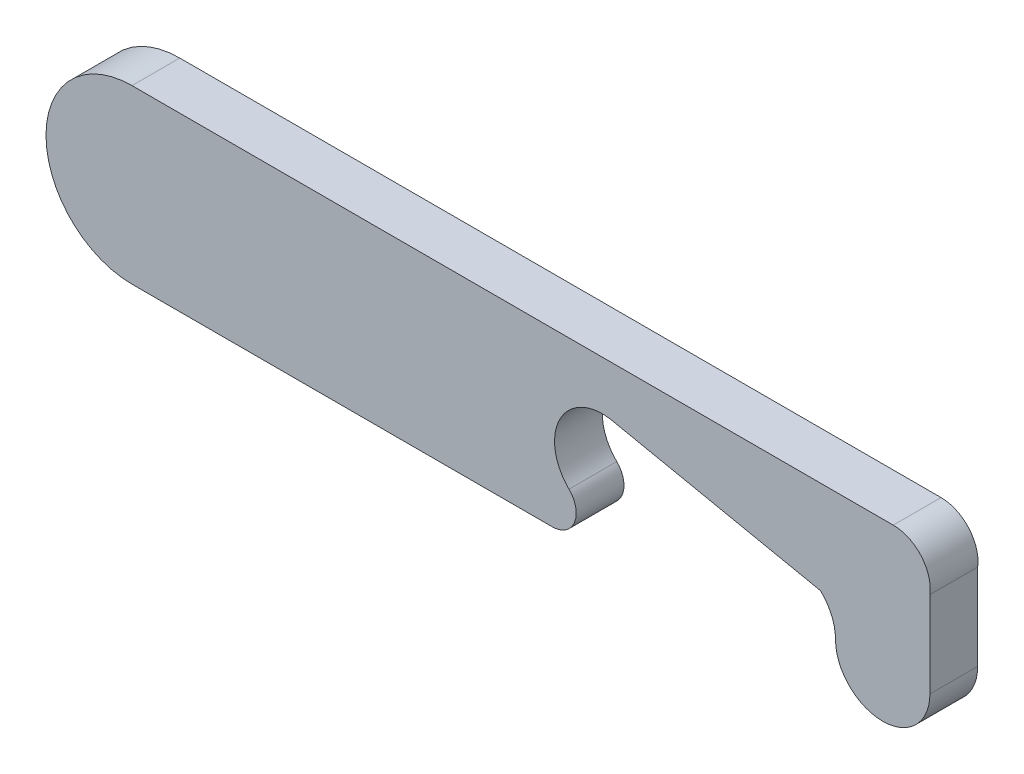
SolidWorks part; units mm, degrees
ref_plane "Front Plane" through (0, 0, 0) normal (0, 0, 1) x (1, 0, 0)
ref_plane "Top Plane" through (0, 0, 0) normal (0, 1, 0) x (1, 0, 0)
ref_plane "Right Plane" through (0, 0, 0) normal (1, 0, 0) x (0, 0, -1)
sketch "Sketch1" plane through (0, 0, 0) normal (0, 0, 1) x (1, 0, 0)
  line L0 (5907.5127, 7762.3379) -> (85590.0392, 7762.3379)
  line L1 (5907.5127, -10237.6621) -> (49907.5127, -10237.6621)
  line L2 (89426.8888, 3372.6088) -> (89426.8888, -5627.3912)
  line L3 (77975.854, -1988.2595) -> (55942.7258, 2571.4841)
  line L4 (77927.7242, -2080.418) -> (55924.558, 2473.125)
  line L5 (89526.8888, 3365.9312) -> (89526.8888, -5627.3912)
  line L6 (5907.5127, 7862.3379) -> (85590.0392, 7862.3379)
  line L7 (5907.5127, -10337.6621) -> (49907.5127, -10337.6621)
  line L8 (5907.5127, 8962.3379) -> (85590.0392, 8962.3379)
  line L9 (90626.8888, 3297.4177) -> (90626.8888, -5627.3912)
  line L10 (77375.2124, -3089.3845) -> (55726.3013, 1390.8456)
  line L11 (5907.5127, -11437.6621) -> (49907.5127, -11437.6621)
  line L12 (77322.5099, -3180.5967) -> (55708.446, 1292.4218)
  line L13 (5907.5127, -11537.6621) -> (49907.5127, -11537.6621)
  line L14 (5907.5127, 9062.3379) -> (85590.0392, 9062.3379)
  line L15 (90726.8888, 3291.5776) -> (90726.8888, -5627.3912)
  arc A0 (5907.5127, 7762.3379) -> (5907.5127, -10237.6621) centre (5907.5127, -1237.6621) ccw
  arc A1 (85590.0392, 7762.3379) -> (89426.8888, 3372.6088) centre (85590.0392, 3890.6711) cw
  arc A2 (89426.8888, -5627.3912) -> (79547.0465, -5627.3912) centre (84486.9677, -5627.3912) cw
  arc A3 (79547.0465, -5627.3912) -> (77975.854, -1988.2595) centre (74547.0465, -5627.3912) ccw
  arc A4 (49907.5127, -10237.6621) -> (51651.337, -5946.2725) centre (49907.5127, -7737.6621) ccw
  arc A5 (51651.337, -5946.2725) -> (55942.7258, 2571.4841) centre (55138.9856, -2363.4933) cw
  circle A6 centre (5907.5127, -1237.6621) radius 5342.8075
  arc A7 (51721.09, -5874.6169) -> (55924.558, 2473.125) centre (55138.9856, -2363.4933) cw
  arc A8 (79447.0465, -5627.3912) -> (77927.7242, -2080.418) centre (74547.0465, -5627.3912) ccw
  arc A9 (89526.8888, -5627.3912) -> (79447.0465, -5627.3912) centre (84486.9677, -5627.3912) cw
  arc A10 (85590.0392, 7862.3379) -> (89526.8888, 3365.9312) centre (85590.0392, 3890.6711) cw
  arc A11 (5907.5127, 7862.3379) -> (5907.5127, -10337.6621) centre (5907.5127, -1237.6621) ccw
  arc A12 (49907.5127, -10337.6621) -> (51721.09, -5874.6169) centre (49907.5127, -7737.6621) ccw
  arc A13 (85590.0392, 8962.3379) -> (90626.8888, 3297.4177) centre (85590.0392, 3890.6711) cw
  arc A14 (90626.8888, -5627.3912) -> (78347.0465, -5627.3912) centre (84486.9677, -5627.3912) cw
  arc A15 (78347.0465, -5627.3912) -> (77375.2124, -3089.3845) centre (74547.0465, -5627.3912) ccw
  arc A16 (52488.3727, -5086.4055) -> (55726.3013, 1390.8456) centre (55138.9856, -2363.4933) cw
  arc A17 (49907.5127, -11437.6621) -> (52488.3727, -5086.4055) centre (49907.5127, -7737.6621) ccw
  arc A18 (5907.5127, 8962.3379) -> (5907.5127, -11437.6621) centre (5907.5127, -1237.6621) ccw
  arc A19 (52558.1256, -5014.7499) -> (55708.446, 1292.4218) centre (55138.9856, -2363.4933) cw
  arc A20 (49907.5127, -11537.6621) -> (52558.1256, -5014.7499) centre (49907.5127, -7737.6621) ccw
  arc A21 (5907.5127, 9062.3379) -> (5907.5127, -11537.6621) centre (5907.5127, -1237.6621) ccw
  arc A22 (85590.0392, 9062.3379) -> (90726.8888, 3291.5776) centre (85590.0392, 3890.6711) cw
  arc A23 (90726.8888, -5627.3912) -> (78247.0465, -5627.3912) centre (84486.9677, -5627.3912) cw
  arc A24 (78247.0465, -5627.3912) -> (77322.5099, -3180.5967) centre (74547.0465, -5627.3912) ccw
  dimension "D1" = 1200
extrude "Boss-Extrude2" add sketch "Sketch1" along normal blind 5000 contours A1 L2 A2 A3 L3 A5 A4 L1 A0 L0
sketch "Sketch3" plane through (0, 0, 5000) normal (0, 0, 1) x (1, 0, 0)
  line L8 (85590.0392, 6562.3379) -> (5907.5127, 6562.3379)
  line L9 (5907.5127, -9037.6621) -> (49907.5127, -9037.6621)
  line L10 (56162.213, 3751.4888) -> (78532.4543, -878.0202)
  line L11 (88226.8888, -5627.3912) -> (88226.8888, 3460.7556)
  line L12 (85590.0392, 6562.3379) -> (5907.5127, 6562.3379)
  line L13 (5907.5127, -9037.6621) -> (49907.5127, -9037.6621)
  line L14 (56162.213, 3751.4888) -> (78532.4543, -878.0202)
  line L15 (88226.8888, -5627.3912) -> (88226.8888, 3460.7556)
  arc A12 (5907.5127, 6562.3379) -> (5907.5127, -9037.6621) centre (5907.5127, -1237.6621) ccw
  arc A13 (49907.5127, -9037.6621) -> (50814.3013, -6806.1395) centre (49907.5127, -7737.6621) ccw
  arc A14 (56162.213, 3751.4888) -> (50814.3013, -6806.1395) centre (55138.9856, -2363.4933) ccw
  arc A15 (80747.0465, -5627.3912) -> (78532.4543, -878.0202) centre (74547.0465, -5627.3912) ccw
  arc A16 (80747.0465, -5627.3912) -> (88226.8888, -5627.3912) centre (84486.9677, -5627.3912) ccw
  arc A17 (88226.8888, 3460.7556) -> (85590.0392, 6562.3379) centre (85590.0392, 3890.6711) ccw
  arc A18 (5907.5127, 6562.3379) -> (5907.5127, -9037.6621) centre (5907.5127, -1237.6621) ccw
  arc A19 (49907.5127, -9037.6621) -> (50814.3013, -6806.1395) centre (49907.5127, -7737.6621) ccw
  arc A20 (56162.213, 3751.4888) -> (50814.3013, -6806.1395) centre (55138.9856, -2363.4933) ccw
  arc A21 (80747.0465, -5627.3912) -> (78532.4543, -878.0202) centre (74547.0465, -5627.3912) ccw
  arc A22 (80747.0465, -5627.3912) -> (88226.8888, -5627.3912) centre (84486.9677, -5627.3912) ccw
  arc A23 (88226.8888, 3460.7556) -> (85590.0392, 6562.3379) centre (85590.0392, 3890.6711) ccw
  dimension "D1" = 1200
extrude "Boss-Extrude6" add sketch "Sketch3" against normal blind 1212 contours A18 L13 A19 A20 L14 A21 A22 L15 A23 L12
sketch3d "3DSketch1"
  line L0 (88426.8888, -5627.3912, 5000) -> (88426.8888, 3439.8153, 5000)
  line L1 (85590.0392, 6762.3379, 5000) -> (5907.5127, 6762.3379, 5000)
  line L2 (5907.5127, -9237.6621, 5000) -> (49907.5127, -9237.6621, 5000)
  line L3 (56124.51, 3555.0535, 5000) -> (78455.6391, -1066.3612, 5000)
  line L4 (88426.8888, -5627.3912, 5000) -> (88426.8888, 3439.8153, 5000)
  line L5 (85590.0392, 6762.3379, 5000) -> (5907.5127, 6762.3379, 5000)
  line L6 (5907.5127, -9237.6621, 5000) -> (49907.5127, -9237.6621, 5000)
  line L7 (56124.51, 3555.0535, 5000) -> (78455.6391, -1066.3612, 5000)
  spline S0 degree 5 poles (88025.4847, 466.9342, 5000) (88107.5619, 1074.8306, 5000) (88189.6419, 1682.7273, 5000) (88271.7218, 2290.624, 5000) (88355.6023, 2911.8559, 5000) (88439.4828, 3533.0879, 5000) (88441.2434, 3546.4282, 5000) (88447.6094, 3596.9969, 5000) (88452.2549, 3647.7815, 5000) (88454.8905, 3685.2412, 5000) (88460.1742, 3784.3107, 5000) (88462.0626, 3883.4754, 5000) (88461.7751, 3945.0906, 5000) (88457.6512, 4078.8264, 5000) (88445.2189, 4212.1377, 5000) (88436.1661, 4283.8517, 5000) (88413.5231, 4426.6259, 5000) (88382.1075, 4567.6862, 5000) (88364.2131, 4637.6976, 5000) (88324.0642, 4776.5019, 5000) (88275.2213, 4912.5083, 5000) (88248.666, 4979.7228, 5000) (88191.3666, 5112.3967, 5000) (88125.8478, 5241.2037, 5000) (88091.0782, 5304.557, 5000) (88017.6078, 5428.9969, 5000) (87936.4531, 5548.5695, 5000) (87894.011, 5607.062, 5000) (87805.5097, 5721.3051, 5000) (87709.9992, 5829.7565, 5000) (87660.5568, 5882.4645, 5000) (87558.4276, 5984.7059, 5000) (87450.0701, 6080.319, 5000) (87394.4075, 6126.4088, 5000) (87280.2617, 6215.0353, 5000) (87160.7675, 6296.3168, 5000) (87099.7638, 6335.0665, 5000) (86975.4044, 6408.6741, 5000) (86846.663, 6474.2787, 5000) (86781.2824, 6505.0538, 5000) (86648.6725, 6562.4967, 5000) (86512.7073, 6611.6191, 5000) (86443.9787, 6634.0181, 5000) (86305.215, 6674.3273, 5000) (86164.2091, 6705.3306, 5000) (86093.231, 6718.6845, 5000) (85974.2843, 6737.6593, 5000) (85854.4917, 6751.6614, 5000) (85806.4774, 6756.1979, 5000) (85441.4271, 6780.5237, 5000) (85075.1689, 6712.4891, 5000) (84760.2357, 6889.881, 5000) (84452.3983, 7609.8432, 5000) (84155.66, 9178.4791, 5000) knots -0.604775 -0.604775 -0.604775 -0.604775 -0.604775 -0.604775 0.013549 0.013549 0.013549 0.027113 0.027113 0.027113 0.064927 0.064927 0.064927 0.126992 0.126992 0.126992 0.199742 0.199742 0.199742 0.272493 0.272493 0.272493 0.345244 0.345244 0.345244 0.417994 0.417994 0.417994 0.490745 0.490745 0.490745 0.563496 0.563496 0.563496 0.636246 0.636246 0.636246 0.708997 0.708997 0.708997 0.781748 0.781748 0.781748 0.854499 0.854499 0.854499 0.927249 0.927249 0.927249 0.97575 0.97575 0.97575 1.295543 1.295543 1.295543 1.295543 1.295543 1.295543 only from (88426.8888, 3439.8153, 5000) to (85590.0392, 6762.3379, 5000)
  spline S1 degree 5 poles (8331.8503, 8203.4476, 5000) (7789.052, 7220.1856, 5000) (7238.9422, 6795.9859, 5000) (6684.2923, 6718.9344, 5000) (5993.6489, 6791.1523, 5000) (5304.5506, 6745.2329, 5000) (5170.7906, 6732.595, 5000) (4837.0678, 6693.5874, 5000) (4505.7016, 6640.7265, 5000) (4307.968, 6603.5247, 5000) (3915.1485, 6517.1547, 5000) (3528.575, 6404.8597, 5000) (3337.1082, 6342.4598, 5000) (2958.3313, 6205.6126, 5000) (2588.9014, 6045.586, 5000) (2406.7616, 5959.8516, 5000) (2048.1089, 5777.0878, 5000) (1701.6637, 5572.0289, 5000) (1531.7173, 5464.0785, 5000) (1198.8257, 5237.6413, 5000) (880.8339, 4990.7422, 5000) (725.7672, 4862.3436, 5000) (423.9006, 4595.9809, 5000) (139.3845, 4311.1528, 5000) (1.6455, 4164.3166, 5000) (-264.4311, 3862.1885, 5000) (-510.979, 3543.9259, 5000) (-629.2149, 3380.9755, 5000) (-855.2993, 3047.8655, 5000) (-1059.9855, 2701.1951, 5000) (-1156.8513, 2524.7024, 5000) (-1339.3735, 2165.8673, 5000) (-1498.9657, 1796.2632, 5000) (-1572.9318, 1609.0157, 5000) (-1709.0094, 1230.1229, 5000) (-1820.9875, 843.4219, 5000) (-1870.8859, 648.3762, 5000) (-1958.37, 255.4088, 5000) (-2020.9657, -142.2828, 5000) (-2046.0084, -342.0464, 5000) (-2083.5176, -742.8829, 5000) (-2095.7424, -1145.2849, 5000) (-2095.5339, -1346.612, 5000) (-2082.4759, -1748.9878, 5000) (-2044.1367, -2149.7458, 5000) (-2018.6804, -2349.4571, 5000) (-1955.2613, -2747.0183, 5000) (-1866.9637, -3139.8037, 5000) (-1816.6615, -3334.7455, 5000) (-1703.8828, -3721.2139, 5000) (-1567.021, -4099.8241, 5000) (-1492.6672, -4286.918, 5000) (-1332.31, -4656.1908, 5000) (-1149.0452, -5014.6472, 5000) (-1051.8141, -5190.9389, 5000) (-846.4105, -5537.1847, 5000) (-619.6368, -5869.8259, 5000) (-501.0636, -6032.5311, 5000) (-253.8573, -6350.2825, 5000) (12.8444, -6651.8589, 5000) (150.8871, -6798.4096, 5000) (435.9925, -7082.6479, 5000) (738.41, -7348.3849, 5000) (893.7423, -7476.4621, 5000) (1212.2446, -7722.7022, 5000) (1545.6043, -7948.4498, 5000) (1715.7738, -8056.0481, 5000) (2062.643, -8260.389, 5000) (2421.6738, -8442.4091, 5000) (2603.9909, -8527.766, 5000) (2973.7513, -8687.0274, 5000) (3352.809, -8823.0923, 5000) (3544.404, -8885.0965, 5000) (3930.1494, -8996.2845, 5000) (4322.0591, -9081.6683, 5000) (4518.7729, -9118.3208, 5000) (4848.0365, -9170.3036, 5000) (5179.5933, -9208.6088, 5000) (5312.2591, -9220.99, 5000) (5997.6873, -9266.0479, 5000) (6684.6307, -9194.3643, 5000) (7236.6852, -9272.9102, 5000) (7784.2158, -9700.0124, 5000) (8324.4681, -10687.8892, 5000) knots -0.097275 -0.097275 -0.097275 -0.097275 -0.097275 -0.097275 0.013342 0.013342 0.013342 0.040026 0.040026 0.040026 0.080053 0.080053 0.080053 0.120079 0.120079 0.120079 0.160105 0.160105 0.160105 0.200132 0.200132 0.200132 0.240158 0.240158 0.240158 0.280184 0.280184 0.280184 0.320211 0.320211 0.320211 0.360237 0.360237 0.360237 0.400263 0.400263 0.400263 0.44029 0.44029 0.44029 0.480316 0.480316 0.480316 0.520342 0.520342 0.520342 0.560369 0.560369 0.560369 0.600395 0.600395 0.600395 0.640421 0.640421 0.640421 0.680448 0.680448 0.680448 0.720474 0.720474 0.720474 0.7605 0.7605 0.7605 0.800527 0.800527 0.800527 0.840553 0.840553 0.840553 0.880579 0.880579 0.880579 0.920606 0.920606 0.920606 0.960413 0.960413 0.960413 0.986877 0.986877 0.986877 1.09698 1.09698 1.09698 1.09698 1.09698 1.09698 only from (5907.5127, 6762.3379, 5000) to (5907.5127, -9237.6621, 5000)
  spline S2 degree 5 poles (48951.5613, -11979.9891, 5000) (49139.6087, -10230.3566, 5000) (49339.8221, -9410.9602, 5000) (49547.8891, -9192.0776, 5000) (49784.7113, -9250.1717, 5000) (50020.5681, -9234.4549, 5000) (50045.6481, -9232.0853, 5000) (50108.2211, -9224.7714, 5000) (50170.3523, -9214.86, 5000) (50207.4273, -9207.8847, 5000) (50281.081, -9191.6903, 5000) (50353.5635, -9170.635, 5000) (50389.4635, -9158.935, 5000) (50460.4842, -9133.2761, 5000) (50529.7523, -9103.2711, 5000) (50563.9035, -9087.1959, 5000) (50631.1509, -9052.9277, 5000) (50696.1094, -9014.4792, 5000) (50727.9743, -8994.2385, 5000) (50790.3915, -8951.7815, 5000) (50850.015, -8905.4879, 5000) (50879.09, -8881.4132, 5000) (50935.69, -8831.4702, 5000) (50989.0367, -8778.0649, 5000) (51014.8628, -8750.5331, 5000) (51064.7522, -8693.8841, 5000) (51110.9799, -8634.2099, 5000) (51133.1491, -8603.6567, 5000) (51175.5399, -8541.1985, 5000) (51213.9186, -8476.1978, 5000) (51232.081, -8443.1055, 5000) (51266.3038, -8375.8239, 5000) (51296.2274, -8306.5231, 5000) (51310.096, -8271.4142, 5000) (51335.6106, -8200.3718, 5000) (51356.6065, -8127.8653, 5000) (51365.9625, -8091.2943, 5000) (51382.3657, -8017.6129, 5000) (51394.1023, -7943.0458, 5000) (51398.7978, -7905.5902, 5000) (51405.8308, -7830.4333, 5000) (51408.1232, -7754.9826, 5000) (51408.0843, -7717.2337, 5000) (51405.6358, -7641.7883, 5000) (51398.4462, -7566.6473, 5000) (51393.6727, -7529.2018, 5000) (51381.7819, -7454.6588, 5000) (51365.23, -7381.0074, 5000) (51355.7998, -7344.4542, 5000) (51334.6528, -7271.9925, 5000) (51308.9765, -7201.0188, 5000) (51295.0298, -7165.9443, 5000) (51264.9668, -7096.7015, 5000) (51230.6593, -7029.4327, 5000) (51212.4485, -6996.3566, 5000) (51174.9172, -6933.13, 5000) (51133.404, -6872.5157, 5000) (51112.3439, -6843.5984, 5000) (51076.3641, -6796.8378, 5000) (51038.544, -6751.484, 5000) (51023.3108, -6733.954, 5000) (50872.9498, -6569.5185, 5000) (50676.7719, -6451.0302, 5000) (50694.4894, -6150.8678, 5000) (51135.9063, -5425.8022, 5000) (52231.2577, -4044.9441, 5000) knots -0.279215 -0.279215 -0.279215 -0.279215 -0.279215 -0.279215 0.017688 0.017688 0.017688 0.053065 0.053065 0.053065 0.10613 0.10613 0.10613 0.159195 0.159195 0.159195 0.21226 0.21226 0.21226 0.265325 0.265325 0.265325 0.31839 0.31839 0.31839 0.371455 0.371455 0.371455 0.42452 0.42452 0.42452 0.477585 0.477585 0.477585 0.53065 0.53065 0.53065 0.583715 0.583715 0.583715 0.63678 0.63678 0.63678 0.689845 0.689845 0.689845 0.74291 0.74291 0.74291 0.795976 0.795976 0.795976 0.849041 0.849041 0.849041 0.902106 0.902106 0.902106 0.952425 0.952425 0.952425 0.985057 0.985057 0.985057 1.265751 1.265751 1.265751 1.265751 1.265751 1.265751 only from (49907.5127, -9237.6621, 5000) to (50953.8073, -6662.8283, 5000)
  spline S3 degree 5 poles (51250.0046, -9422.1078, 5000) (51742.7709, -8246.7236, 5000) (51767.5921, -7539.6368, 5000) (51498.5986, -7126.5862, 5000) (51028.9011, -6772.177, 5000) (50638.7137, -6338.1979, 5000) (50573.4403, -6261.4299, 5000) (50414.4987, -6065.8803, 5000) (50264.071, -5864.1187, 5000) (50177.2676, -5740.682, 5000) (50011.344, -5488.7628, 5000) (49862.3397, -5226.1787, 5000) (49792.0866, -5092.4786, 5000) (49660.1167, -4820.7785, 5000) (49545.2963, -4541.5113, 5000) (49492.2631, -4400.1502, 5000) (49395.1295, -4114.3017, 5000) (49316.2199, -3822.8577, 5000) (49281.3618, -3675.9363, 5000) (49220.9202, -3380.0938, 5000) (49179.1907, -3081.0495, 5000) (49163.0266, -2930.9232, 5000) (49140.1454, -2629.8547, 5000) (49136.2486, -2327.9394, 5000) (49139.0423, -2176.9694, 5000) (49154.1057, -1875.4034, 5000) (49188.105, -1575.3829, 5000) (49209.81, -1425.9558, 5000) (49262.5741, -1128.6614, 5000) (49333.932, -835.2738, 5000) (49374.2063, -689.7486, 5000) (49463.8394, -401.4186, 5000) (49571.4292, -119.2969, 5000) (49629.6366, 20.0283, 5000) (49754.723, 294.8403, 5000) (49896.8457, 561.241, 5000) (49972.067, 692.1661, 5000) (50130.6314, 949.1204, 5000) (50305.0427, 1195.5933, 5000) (50396.0901, 1316.0507, 5000) (50585.6286, 1551.0898, 5000) (50789.5743, 1773.743, 5000) (50895.0101, 1881.8306, 5000) (51112.5295, 2091.2429, 5000) (51342.789, 2286.5593, 5000) (51460.9481, 2380.5699, 5000) (51703.0136, 2561.0486, 5000) (51955.9511, 2725.9478, 5000) (52084.9677, 2804.3982, 5000) (52347.7567, 2953.0924, 5000) (52619.3767, 3084.9564, 5000) (52757.2132, 3146.6028, 5000) (53036.5761, 3261.168, 5000) (53322.5936, 3357.966, 5000) (53467.0747, 3401.8537, 5000) (53758.599, 3480.4671, 5000) (54054.4821, 3540.4787, 5000) (54203.3207, 3565.8443, 5000) (54502.4069, 3607.3159, 5000) (54803.5401, 3630.3094, 5000) (54954.4068, 3637.0146, 5000) (55212.4714, 3639.9918, 5000) (55470.1749, 3627.9595, 5000) (55577.0231, 3620.6345, 5000) (55740.2773, 3606.2487, 5000) (55903.0379, 3587.5975, 5000) (55959.3434, 3580.4727, 5000) (56021.9303, 3571.6306, 5000) (56084.3263, 3561.5938, 5000) (56090.7093, 3560.5585, 5000) (56691.8277, 3462.6567, 5000) (57292.9461, 3364.755, 5000) (57887.6823, 3267.8926, 5000) (58482.3908, 3171.0307, 5000) (59085.5645, 3074.0754, 5000) knots -0.142129 -0.142129 -0.142129 -0.142129 -0.142129 -0.142129 0.016537 0.016537 0.016537 0.049611 0.049611 0.049611 0.099222 0.099222 0.099222 0.148832 0.148832 0.148832 0.198443 0.198443 0.198443 0.248054 0.248054 0.248054 0.297665 0.297665 0.297665 0.347275 0.347275 0.347275 0.396886 0.396886 0.396886 0.446497 0.446497 0.446497 0.496108 0.496108 0.496108 0.545718 0.545718 0.545718 0.595329 0.595329 0.595329 0.64494 0.64494 0.64494 0.694551 0.694551 0.694551 0.744162 0.744162 0.744162 0.793772 0.793772 0.793772 0.843383 0.843383 0.843383 0.892994 0.892994 0.892994 0.942605 0.942605 0.942605 0.977806 0.977806 0.977806 0.99647 0.99647 0.99647 0.998598 0.998598 0.998598 1.196839 1.196839 1.196839 1.196839 1.196839 1.196839 only from (50953.8073, -6662.8283, 5000) to (56124.51, 3555.0535, 5000)
  spline S4 degree 5 poles (76272.216, 990.8707, 5000) (76750.0959, 540.6099, 5000) (77227.9758, 90.3491, 5000) (77705.8557, -359.9116, 5000) (78201.3951, -826.8113, 5000) (78696.9345, -1293.7109, 5000) (78714.551, -1310.3947, 5000) (78785.9288, -1378.6911, 5000) (78855.1659, -1449.2212, 5000) (78906.3562, -1503.478, 5000) (79040.9462, -1650.7948, 5000) (79170.603, -1802.4318, 5000) (79249.5618, -1899.19, 5000) (79418.4048, -2117.1637, 5000) (79573.6566, -2345.2415, 5000) (79654.5211, -2472.7992, 5000) (79808.0466, -2732.9004, 5000) (79945.1002, -3001.909, 5000) (80009.4274, -3138.4877, 5000) (80129.5193, -3415.4885, 5000) (80232.1598, -3699.5661, 5000) (80278.9526, -3843.1732, 5000) (80363.1546, -4133.1225, 5000) (80427.931, -4427.7383, 5000) (80455.8343, -4576.0365, 5000) (80495.4843, -4824.5569, 5000) (80524.7402, -5074.8487, 5000) (80534.2185, -5175.169, 5000) (80573.0209, -5757.4959, 5000) (80499.344, -6341.2883, 5000) (80607.7005, -6822.178, 5000) (81131.7304, -7297.652, 5000) (82317.7822, -7764.5005, 5000) knots -0.580161 -0.580161 -0.580161 -0.580161 -0.580161 -0.580161 0.05473 0.05473 0.05473 0.078192 0.078192 0.078192 0.150258 0.150258 0.150258 0.270929 0.270929 0.270929 0.416744 0.416744 0.416744 0.562558 0.562558 0.562558 0.708372 0.708372 0.708372 0.854186 0.854186 0.854186 0.951395 0.951395 0.951395 1.417761 1.417761 1.417761 1.417761 1.417761 1.417761 only from (78455.6391, -1066.3612, 5000) to (80547.0465, -5627.3912, 5000)
  spline S5 degree 5 poles (78368.1803, -3915.8644, 5000) (79797.4706, -4277.739, 5000) (80445.4406, -4649.7544, 5000) (80596.8291, -5028.215, 5000) (80525.9705, -5475.0312, 5000) (80555.2574, -5920.5477, 5000) (80561.355, -5985.8843, 5000) (80580.2199, -6149.1727, 5000) (80605.8209, -6311.3318, 5000) (80623.8719, -6408.2114, 5000) (80665.9226, -6601.2231, 5000) (80720.6816, -6791.1989, 5000) (80751.2181, -6885.5575, 5000) (80818.2287, -7072.2398, 5000) (80896.6634, -7254.3431, 5000) (80938.7008, -7344.1325, 5000) (81028.3439, -7520.9516, 5000) (81128.9798, -7691.7812, 5000) (81181.9709, -7775.5881, 5000) (81293.1494, -7939.7644, 5000) (81414.4202, -8096.6237, 5000) (81477.497, -8173.1233, 5000) (81608.3698, -8322.0609, 5000) (81748.3544, -8462.4725, 5000) (81820.5291, -8530.4572, 5000) (81969.0525, -8661.8051, 5000) (82125.542, -8783.5518, 5000) (82205.6727, -8841.9479, 5000) (82369.4952, -8953.6318, 5000) (82540.0178, -9054.791, 5000) (82626.8398, -9102.6764, 5000) (82803.376, -9192.9325, 5000) (82985.2392, -9271.9068, 5000) (83077.3811, -9308.5253, 5000) (83263.8429, -9375.9284, 5000) (83454.1748, -9431.4708, 5000) (83550.1817, -9456.2441, 5000) (83743.6247, -9499.7299, 5000) (83939.4196, -9530.9631, 5000) (84037.7755, -9543.5001, 5000) (84235.1448, -9562.3818, 5000) (84433.3109, -9568.8127, 5000) (84532.4626, -9568.9154, 5000) (84730.6416, -9562.8948, 5000) (84928.0496, -9544.4219, 5000) (85026.4312, -9532.0886, 5000) (85222.2904, -9501.2609, 5000) (85415.823, -9458.1758, 5000) (85511.881, -9433.6013, 5000) (85702.3275, -9378.4532, 5000) (85888.9284, -9311.4364, 5000) (85981.146, -9275.0088, 5000) (86163.1724, -9196.4112, 5000) (86339.8951, -9106.5208, 5000) (86426.816, -9058.8153, 5000) (86597.5478, -8958.0094, 5000) (86761.6012, -8846.6651, 5000) (86841.8527, -8788.435, 5000) (86998.5939, -8667.0126, 5000) (87147.389, -8535.9725, 5000) (87219.7043, -8468.1375, 5000) (87359.9794, -8328.0161, 5000) (87491.1604, -8179.3497, 5000) (87554.3954, -8102.9809, 5000) (87675.9908, -7946.3731, 5000) (87787.5089, -7782.4273, 5000) (87840.6734, -7698.7303, 5000) (87941.6629, -7528.1095, 5000) (88031.6722, -7351.4766, 5000) (88073.8956, -7261.7745, 5000) (88152.7071, -7079.8339, 5000) (88220.103, -6893.2901, 5000) (88250.8344, -6798.9945, 5000) (88306.1385, -6608.6109, 5000) (88348.6749, -6415.1512, 5000) (88366.9964, -6317.7693, 5000) (88393.0299, -6154.5747, 5000) (88412.2408, -5990.2195, 5000) (88418.4648, -5924.344, 5000) (88448.3211, -5476.2995, 5000) (88376.7701, -5026.9287, 5000) (88526.822, -4646.4701, 5000) (89172.7625, -4272.4968, 5000) (90599.4101, -3908.7337, 5000) knots -0.140653 -0.140653 -0.140653 -0.140653 -0.140653 -0.140653 0.013123 0.013123 0.013123 0.039587 0.039587 0.039587 0.079394 0.079394 0.079394 0.119421 0.119421 0.119421 0.159447 0.159447 0.159447 0.199473 0.199473 0.199473 0.2395 0.2395 0.2395 0.279526 0.279526 0.279526 0.319552 0.319552 0.319552 0.359579 0.359579 0.359579 0.399605 0.399605 0.399605 0.439631 0.439631 0.439631 0.479658 0.479658 0.479658 0.519684 0.519684 0.519684 0.55971 0.55971 0.55971 0.599737 0.599737 0.599737 0.639763 0.639763 0.639763 0.679789 0.679789 0.679789 0.719816 0.719816 0.719816 0.759842 0.759842 0.759842 0.799868 0.799868 0.799868 0.839895 0.839895 0.839895 0.879921 0.879921 0.879921 0.919947 0.919947 0.919947 0.959974 0.959974 0.959974 0.986658 0.986658 0.986658 1.14124 1.14124 1.14124 1.14124 1.14124 1.14124 only from (80547.0465, -5627.3912, 5000) to (88426.8888, -5627.3912, 5000)
  spline S6 degree 5 poles (88426.8888, 3439.8153, 5000) (88428.6874, 3453.1357, 5000) (88430.486, 3466.4562, 5000) (88432.2845, 3479.7766, 5000) (88435.8836, 3506.4322, 5000) (88439.4828, 3533.0879, 5000) (88441.2434, 3546.4282, 5000) (88447.6094, 3596.9969, 5000) (88452.2549, 3647.7815, 5000) (88454.8905, 3685.2412, 5000) (88460.1742, 3784.3107, 5000) (88462.0626, 3883.4754, 5000) (88461.7751, 3945.0906, 5000) (88457.6512, 4078.8264, 5000) (88445.2189, 4212.1377, 5000) (88436.1661, 4283.8517, 5000) (88413.5231, 4426.6259, 5000) (88382.1075, 4567.6862, 5000) (88364.2131, 4637.6976, 5000) (88324.0642, 4776.5019, 5000) (88275.2213, 4912.5083, 5000) (88248.666, 4979.7228, 5000) (88191.3666, 5112.3967, 5000) (88125.8478, 5241.2037, 5000) (88091.0782, 5304.557, 5000) (88017.6078, 5428.9969, 5000) (87936.4531, 5548.5695, 5000) (87894.011, 5607.062, 5000) (87805.5097, 5721.3051, 5000) (87709.9992, 5829.7565, 5000) (87660.5568, 5882.4645, 5000) (87558.4276, 5984.7059, 5000) (87450.0701, 6080.319, 5000) (87394.4075, 6126.4088, 5000) (87280.2617, 6215.0353, 5000) (87160.7675, 6296.3168, 5000) (87099.7638, 6335.0665, 5000) (86975.4044, 6408.6741, 5000) (86846.663, 6474.2787, 5000) (86781.2824, 6505.0538, 5000) (86648.6725, 6562.4967, 5000) (86512.7073, 6611.6191, 5000) (86443.9787, 6634.0181, 5000) (86305.215, 6674.3273, 5000) (86164.2091, 6705.3306, 5000) (86093.231, 6718.6845, 5000) (85974.2843, 6737.6593, 5000) (85854.4917, 6751.6614, 5000) (85806.4774, 6756.1979, 5000) (85734.3674, 6761.0031, 5000) (85662.2103, 6762.2044, 5000) (85638.1544, 6762.3379, 5000) (85614.0968, 6762.3379, 5000) (85590.0392, 6762.3379, 5000) knots 0 0 0 0 0 0 0.013549 0.013549 0.013549 0.027113 0.027113 0.027113 0.064927 0.064927 0.064927 0.126992 0.126992 0.126992 0.199742 0.199742 0.199742 0.272493 0.272493 0.272493 0.345244 0.345244 0.345244 0.417994 0.417994 0.417994 0.490745 0.490745 0.490745 0.563496 0.563496 0.563496 0.636246 0.636246 0.636246 0.708997 0.708997 0.708997 0.781748 0.781748 0.781748 0.854499 0.854499 0.854499 0.927249 0.927249 0.927249 0.97575 0.97575 0.97575 1 1 1 1 1 1
  spline S7 degree 5 poles (5907.5127, 6762.3379, 5000) (5840.4921, 6762.3379, 5000) (5773.4714, 6762.3379, 5000) (5706.4556, 6761.966, 5000) (5505.4375, 6758.6194, 5000) (5304.5506, 6745.2329, 5000) (5170.7906, 6732.595, 5000) (4837.0678, 6693.5874, 5000) (4505.7016, 6640.7265, 5000) (4307.968, 6603.5247, 5000) (3915.1485, 6517.1547, 5000) (3528.575, 6404.8597, 5000) (3337.1082, 6342.4598, 5000) (2958.3313, 6205.6126, 5000) (2588.9014, 6045.586, 5000) (2406.7616, 5959.8516, 5000) (2048.1089, 5777.0878, 5000) (1701.6637, 5572.0289, 5000) (1531.7173, 5464.0785, 5000) (1198.8257, 5237.6413, 5000) (880.8339, 4990.7422, 5000) (725.7672, 4862.3436, 5000) (423.9006, 4595.9809, 5000) (139.3845, 4311.1528, 5000) (1.6455, 4164.3166, 5000) (-264.4311, 3862.1885, 5000) (-510.979, 3543.9259, 5000) (-629.2149, 3380.9755, 5000) (-855.2993, 3047.8655, 5000) (-1059.9855, 2701.1951, 5000) (-1156.8513, 2524.7024, 5000) (-1339.3735, 2165.8673, 5000) (-1498.9657, 1796.2632, 5000) (-1572.9318, 1609.0157, 5000) (-1709.0094, 1230.1229, 5000) (-1820.9875, 843.4219, 5000) (-1870.8859, 648.3762, 5000) (-1958.37, 255.4088, 5000) (-2020.9657, -142.2828, 5000) (-2046.0084, -342.0464, 5000) (-2083.5176, -742.8829, 5000) (-2095.7424, -1145.2849, 5000) (-2095.5339, -1346.612, 5000) (-2082.4759, -1748.9878, 5000) (-2044.1367, -2149.7458, 5000) (-2018.6804, -2349.4571, 5000) (-1955.2613, -2747.0183, 5000) (-1866.9637, -3139.8037, 5000) (-1816.6615, -3334.7455, 5000) (-1703.8828, -3721.2139, 5000) (-1567.021, -4099.8241, 5000) (-1492.6672, -4286.918, 5000) (-1332.31, -4656.1908, 5000) (-1149.0452, -5014.6472, 5000) (-1051.8141, -5190.9389, 5000) (-846.4105, -5537.1847, 5000) (-619.6368, -5869.8259, 5000) (-501.0636, -6032.5311, 5000) (-253.8573, -6350.2825, 5000) (12.8444, -6651.8589, 5000) (150.8871, -6798.4096, 5000) (435.9925, -7082.6479, 5000) (738.41, -7348.3849, 5000) (893.7423, -7476.4621, 5000) (1212.2446, -7722.7022, 5000) (1545.6043, -7948.4498, 5000) (1715.7738, -8056.0481, 5000) (2062.643, -8260.389, 5000) (2421.6738, -8442.4091, 5000) (2603.9909, -8527.766, 5000) (2973.7513, -8687.0274, 5000) (3352.809, -8823.0923, 5000) (3544.404, -8885.0965, 5000) (3930.1494, -8996.2845, 5000) (4322.0591, -9081.6683, 5000) (4518.7729, -9118.3208, 5000) (4848.0365, -9170.3036, 5000) (5179.5933, -9208.6088, 5000) (5312.2591, -9220.99, 5000) (5510.947, -9234.0511, 5000) (5709.7622, -9237.3028, 5000) (5775.6759, -9237.6621, 5000) (5841.5943, -9237.6621, 5000) (5907.5127, -9237.6621, 5000) knots 0 0 0 0 0 0 0.013342 0.013342 0.013342 0.040026 0.040026 0.040026 0.080053 0.080053 0.080053 0.120079 0.120079 0.120079 0.160105 0.160105 0.160105 0.200132 0.200132 0.200132 0.240158 0.240158 0.240158 0.280184 0.280184 0.280184 0.320211 0.320211 0.320211 0.360237 0.360237 0.360237 0.400263 0.400263 0.400263 0.44029 0.44029 0.44029 0.480316 0.480316 0.480316 0.520342 0.520342 0.520342 0.560369 0.560369 0.560369 0.600395 0.600395 0.600395 0.640421 0.640421 0.640421 0.680448 0.680448 0.680448 0.720474 0.720474 0.720474 0.7605 0.7605 0.7605 0.800527 0.800527 0.800527 0.840553 0.840553 0.840553 0.880579 0.880579 0.880579 0.920606 0.920606 0.920606 0.960413 0.960413 0.960413 0.986877 0.986877 0.986877 1 1 1 1 1 1
  spline S8 degree 5 poles (49907.5127, -9237.6621, 5000) (49920.0791, -9237.6621, 5000) (49932.6454, -9237.6621, 5000) (49945.2109, -9237.5924, 5000) (49982.9018, -9236.9649, 5000) (50020.5681, -9234.4549, 5000) (50045.6481, -9232.0853, 5000) (50108.2211, -9224.7714, 5000) (50170.3523, -9214.86, 5000) (50207.4273, -9207.8847, 5000) (50281.081, -9191.6903, 5000) (50353.5635, -9170.635, 5000) (50389.4635, -9158.935, 5000) (50460.4842, -9133.2761, 5000) (50529.7523, -9103.2711, 5000) (50563.9035, -9087.1959, 5000) (50631.1509, -9052.9277, 5000) (50696.1094, -9014.4792, 5000) (50727.9743, -8994.2385, 5000) (50790.3915, -8951.7815, 5000) (50850.015, -8905.4879, 5000) (50879.09, -8881.4132, 5000) (50935.69, -8831.4702, 5000) (50989.0367, -8778.0649, 5000) (51014.8628, -8750.5331, 5000) (51064.7522, -8693.8841, 5000) (51110.9799, -8634.2099, 5000) (51133.1491, -8603.6567, 5000) (51175.5399, -8541.1985, 5000) (51213.9186, -8476.1978, 5000) (51232.081, -8443.1055, 5000) (51266.3038, -8375.8239, 5000) (51296.2274, -8306.5231, 5000) (51310.096, -8271.4142, 5000) (51335.6106, -8200.3718, 5000) (51356.6065, -8127.8653, 5000) (51365.9625, -8091.2943, 5000) (51382.3657, -8017.6129, 5000) (51394.1023, -7943.0458, 5000) (51398.7978, -7905.5902, 5000) (51405.8308, -7830.4333, 5000) (51408.1232, -7754.9826, 5000) (51408.0843, -7717.2337, 5000) (51405.6358, -7641.7883, 5000) (51398.4462, -7566.6473, 5000) (51393.6727, -7529.2018, 5000) (51381.7819, -7454.6588, 5000) (51365.23, -7381.0074, 5000) (51355.7998, -7344.4542, 5000) (51334.6528, -7271.9925, 5000) (51308.9765, -7201.0188, 5000) (51295.0298, -7165.9443, 5000) (51264.9668, -7096.7015, 5000) (51230.6593, -7029.4327, 5000) (51212.4485, -6996.3566, 5000) (51174.9172, -6933.13, 5000) (51133.404, -6872.5157, 5000) (51112.3439, -6843.5984, 5000) (51076.3641, -6796.8378, 5000) (51038.544, -6751.484, 5000) (51023.3108, -6733.954, 5000) (51000.4803, -6708.9865, 5000) (50976.5936, -6685.0783, 5000) (50969.0213, -6677.6384, 5000) (50961.4143, -6670.2334, 5000) (50953.8073, -6662.8283, 5000) knots 0 0 0 0 0 0 0.017688 0.017688 0.017688 0.053065 0.053065 0.053065 0.10613 0.10613 0.10613 0.159195 0.159195 0.159195 0.21226 0.21226 0.21226 0.265325 0.265325 0.265325 0.31839 0.31839 0.31839 0.371455 0.371455 0.371455 0.42452 0.42452 0.42452 0.477585 0.477585 0.477585 0.53065 0.53065 0.53065 0.583715 0.583715 0.583715 0.63678 0.63678 0.63678 0.689845 0.689845 0.689845 0.74291 0.74291 0.74291 0.795976 0.795976 0.795976 0.849041 0.849041 0.849041 0.902106 0.902106 0.902106 0.952425 0.952425 0.952425 0.985057 0.985057 0.985057 1 1 1 1 1 1
  spline S9 degree 5 poles (50953.8073, -6662.8283, 5000) (50917.7893, -6627.7667, 5000) (50881.7712, -6592.705, 5000) (50845.9503, -6557.4461, 5000) (50739.6706, -6450.4854, 5000) (50638.7137, -6338.1979, 5000) (50573.4403, -6261.4299, 5000) (50414.4987, -6065.8803, 5000) (50264.071, -5864.1187, 5000) (50177.2676, -5740.682, 5000) (50011.344, -5488.7628, 5000) (49862.3397, -5226.1787, 5000) (49792.0866, -5092.4786, 5000) (49660.1167, -4820.7785, 5000) (49545.2963, -4541.5113, 5000) (49492.2631, -4400.1502, 5000) (49395.1295, -4114.3017, 5000) (49316.2199, -3822.8577, 5000) (49281.3618, -3675.9363, 5000) (49220.9202, -3380.0938, 5000) (49179.1907, -3081.0495, 5000) (49163.0266, -2930.9232, 5000) (49140.1454, -2629.8547, 5000) (49136.2486, -2327.9394, 5000) (49139.0423, -2176.9694, 5000) (49154.1057, -1875.4034, 5000) (49188.105, -1575.3829, 5000) (49209.81, -1425.9558, 5000) (49262.5741, -1128.6614, 5000) (49333.932, -835.2738, 5000) (49374.2063, -689.7486, 5000) (49463.8394, -401.4186, 5000) (49571.4292, -119.2969, 5000) (49629.6366, 20.0283, 5000) (49754.723, 294.8403, 5000) (49896.8457, 561.241, 5000) (49972.067, 692.1661, 5000) (50130.6314, 949.1204, 5000) (50305.0427, 1195.5933, 5000) (50396.0901, 1316.0507, 5000) (50585.6286, 1551.0898, 5000) (50789.5743, 1773.743, 5000) (50895.0101, 1881.8306, 5000) (51112.5295, 2091.2429, 5000) (51342.789, 2286.5593, 5000) (51460.9481, 2380.5699, 5000) (51703.0136, 2561.0486, 5000) (51955.9511, 2725.9478, 5000) (52084.9677, 2804.3982, 5000) (52347.7567, 2953.0924, 5000) (52619.3767, 3084.9564, 5000) (52757.2132, 3146.6028, 5000) (53036.5761, 3261.168, 5000) (53322.5936, 3357.966, 5000) (53467.0747, 3401.8537, 5000) (53758.599, 3480.4671, 5000) (54054.4821, 3540.4787, 5000) (54203.3207, 3565.8443, 5000) (54502.4069, 3607.3159, 5000) (54803.5401, 3630.3094, 5000) (54954.4068, 3637.0146, 5000) (55212.4714, 3639.9918, 5000) (55470.1749, 3627.9595, 5000) (55577.0231, 3620.6345, 5000) (55740.2773, 3606.2487, 5000) (55903.0379, 3587.5975, 5000) (55959.3434, 3580.4727, 5000) (56021.9303, 3571.6306, 5000) (56084.3263, 3561.5938, 5000) (56090.7093, 3560.5585, 5000) (56101.2988, 3558.8338, 5000) (56111.8883, 3557.1092, 5000) (56116.0956, 3556.424, 5000) (56120.3028, 3555.7387, 5000) (56124.51, 3555.0535, 5000) knots 0 0 0 0 0 0 0.016537 0.016537 0.016537 0.049611 0.049611 0.049611 0.099222 0.099222 0.099222 0.148832 0.148832 0.148832 0.198443 0.198443 0.198443 0.248054 0.248054 0.248054 0.297665 0.297665 0.297665 0.347275 0.347275 0.347275 0.396886 0.396886 0.396886 0.446497 0.446497 0.446497 0.496108 0.496108 0.496108 0.545718 0.545718 0.545718 0.595329 0.595329 0.595329 0.64494 0.64494 0.64494 0.694551 0.694551 0.694551 0.744162 0.744162 0.744162 0.793772 0.793772 0.793772 0.843383 0.843383 0.843383 0.892994 0.892994 0.892994 0.942605 0.942605 0.942605 0.977806 0.977806 0.977806 0.99647 0.99647 0.99647 0.998598 0.998598 0.998598 1 1 1 1 1 1
  spline S10 degree 5 poles (78455.6391, -1066.3612, 5000) (78496.8344, -1105.1756, 5000) (78538.0297, -1143.99, 5000) (78579.225, -1182.8044, 5000) (78638.0797, -1238.2577, 5000) (78696.9345, -1293.7109, 5000) (78714.551, -1310.3947, 5000) (78785.9288, -1378.6911, 5000) (78855.1659, -1449.2212, 5000) (78906.3562, -1503.478, 5000) (79040.9462, -1650.7948, 5000) (79170.603, -1802.4318, 5000) (79249.5618, -1899.19, 5000) (79418.4048, -2117.1637, 5000) (79573.6566, -2345.2415, 5000) (79654.5211, -2472.7992, 5000) (79808.0466, -2732.9004, 5000) (79945.1002, -3001.909, 5000) (80009.4274, -3138.4877, 5000) (80129.5193, -3415.4885, 5000) (80232.1598, -3699.5661, 5000) (80278.9526, -3843.1732, 5000) (80363.1546, -4133.1225, 5000) (80427.931, -4427.7383, 5000) (80455.8343, -4576.0365, 5000) (80495.4843, -4824.5569, 5000) (80524.7402, -5074.8487, 5000) (80534.2185, -5175.169, 5000) (80544.2578, -5325.8346, 5000) (80546.7677, -5476.5983, 5000) (80547.0465, -5526.8602, 5000) (80547.0465, -5577.1257, 5000) (80547.0465, -5627.3912, 5000) knots 0 0 0 0 0 0 0.05473 0.05473 0.05473 0.078192 0.078192 0.078192 0.150258 0.150258 0.150258 0.270929 0.270929 0.270929 0.416744 0.416744 0.416744 0.562558 0.562558 0.562558 0.708372 0.708372 0.708372 0.854186 0.854186 0.854186 0.951395 0.951395 0.951395 1 1 1 1 1 1
  spline S11 degree 5 poles (80547.0465, -5627.3912, 5000) (80547.0465, -5659.8553, 5000) (80547.0465, -5692.3195, 5000) (80547.2235, -5724.7813, 5000) (80548.8249, -5822.6959, 5000) (80555.2574, -5920.5477, 5000) (80561.355, -5985.8843, 5000) (80580.2199, -6149.1727, 5000) (80605.8209, -6311.3318, 5000) (80623.8719, -6408.2114, 5000) (80665.9226, -6601.2231, 5000) (80720.6816, -6791.1989, 5000) (80751.2181, -6885.5575, 5000) (80818.2287, -7072.2398, 5000) (80896.6634, -7254.3431, 5000) (80938.7008, -7344.1325, 5000) (81028.3439, -7520.9516, 5000) (81128.9798, -7691.7812, 5000) (81181.9709, -7775.5881, 5000) (81293.1494, -7939.7644, 5000) (81414.4202, -8096.6237, 5000) (81477.497, -8173.1233, 5000) (81608.3698, -8322.0609, 5000) (81748.3544, -8462.4725, 5000) (81820.5291, -8530.4572, 5000) (81969.0525, -8661.8051, 5000) (82125.542, -8783.5518, 5000) (82205.6727, -8841.9479, 5000) (82369.4952, -8953.6318, 5000) (82540.0178, -9054.791, 5000) (82626.8398, -9102.6764, 5000) (82803.376, -9192.9325, 5000) (82985.2392, -9271.9068, 5000) (83077.3811, -9308.5253, 5000) (83263.8429, -9375.9284, 5000) (83454.1748, -9431.4708, 5000) (83550.1817, -9456.2441, 5000) (83743.6247, -9499.7299, 5000) (83939.4196, -9530.9631, 5000) (84037.7755, -9543.5001, 5000) (84235.1448, -9562.3818, 5000) (84433.3109, -9568.8127, 5000) (84532.4626, -9568.9154, 5000) (84730.6416, -9562.8948, 5000) (84928.0496, -9544.4219, 5000) (85026.4312, -9532.0886, 5000) (85222.2904, -9501.2609, 5000) (85415.823, -9458.1758, 5000) (85511.881, -9433.6013, 5000) (85702.3275, -9378.4532, 5000) (85888.9284, -9311.4364, 5000) (85981.146, -9275.0088, 5000) (86163.1724, -9196.4112, 5000) (86339.8951, -9106.5208, 5000) (86426.816, -9058.8153, 5000) (86597.5478, -8958.0094, 5000) (86761.6012, -8846.6651, 5000) (86841.8527, -8788.435, 5000) (86998.5939, -8667.0126, 5000) (87147.389, -8535.9725, 5000) (87219.7043, -8468.1375, 5000) (87359.9794, -8328.0161, 5000) (87491.1604, -8179.3497, 5000) (87554.3954, -8102.9809, 5000) (87675.9908, -7946.3731, 5000) (87787.5089, -7782.4273, 5000) (87840.6734, -7698.7303, 5000) (87941.6629, -7528.1095, 5000) (88031.6722, -7351.4766, 5000) (88073.8956, -7261.7745, 5000) (88152.7071, -7079.8339, 5000) (88220.103, -6893.2901, 5000) (88250.8344, -6798.9945, 5000) (88306.1385, -6608.6109, 5000) (88348.6749, -6415.1512, 5000) (88366.9964, -6317.7693, 5000) (88393.0299, -6154.5747, 5000) (88412.2408, -5990.2195, 5000) (88418.4648, -5924.344, 5000) (88425.0575, -5825.4092, 5000) (88426.7057, -5726.4098, 5000) (88426.8888, -5693.4052, 5000) (88426.8888, -5660.3982, 5000) (88426.8888, -5627.3912, 5000) knots 0 0 0 0 0 0 0.013123 0.013123 0.013123 0.039587 0.039587 0.039587 0.079394 0.079394 0.079394 0.119421 0.119421 0.119421 0.159447 0.159447 0.159447 0.199473 0.199473 0.199473 0.2395 0.2395 0.2395 0.279526 0.279526 0.279526 0.319552 0.319552 0.319552 0.359579 0.359579 0.359579 0.399605 0.399605 0.399605 0.439631 0.439631 0.439631 0.479658 0.479658 0.479658 0.519684 0.519684 0.519684 0.55971 0.55971 0.55971 0.599737 0.599737 0.599737 0.639763 0.639763 0.639763 0.679789 0.679789 0.679789 0.719816 0.719816 0.719816 0.759842 0.759842 0.759842 0.799868 0.799868 0.799868 0.839895 0.839895 0.839895 0.879921 0.879921 0.879921 0.919947 0.919947 0.919947 0.959974 0.959974 0.959974 0.986658 0.986658 0.986658 1 1 1 1 1 1
  dimension "D1" = 1000
